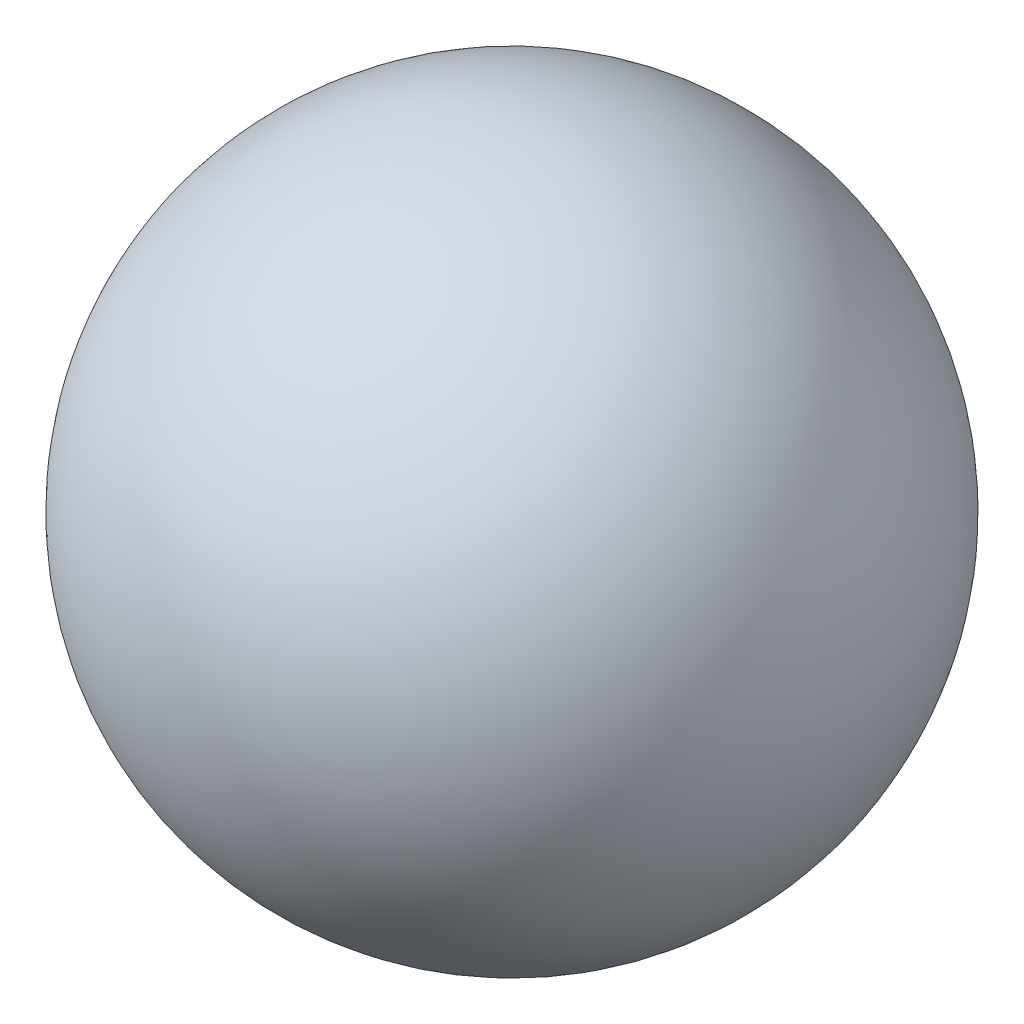
SolidWorks part; units mm, degrees
ref_plane "Front Plane" through (0, 0, 0) normal (0, 0, 1) x (1, 0, 0)
ref_plane "Top Plane" through (0, 0, 0) normal (0, 1, 0) x (1, 0, 0)
ref_plane "Right Plane" through (0, 0, 0) normal (1, 0, 0) x (0, 0, -1)
sketch "Sketch1" plane through (0, 0, 0) normal (0, 0, 1) x (1, 0, 0)
  line L0 (-19.5, 0) -> (19.5, 0)
  arc A0 (-19.5, 0) -> (19.5, 0) centre (0, 0) cw
  dimension "D1" = 19.5
  dimension "D2" = 39
revolve "Revolve1" add sketch "Sketch1" angle 360 about L0
